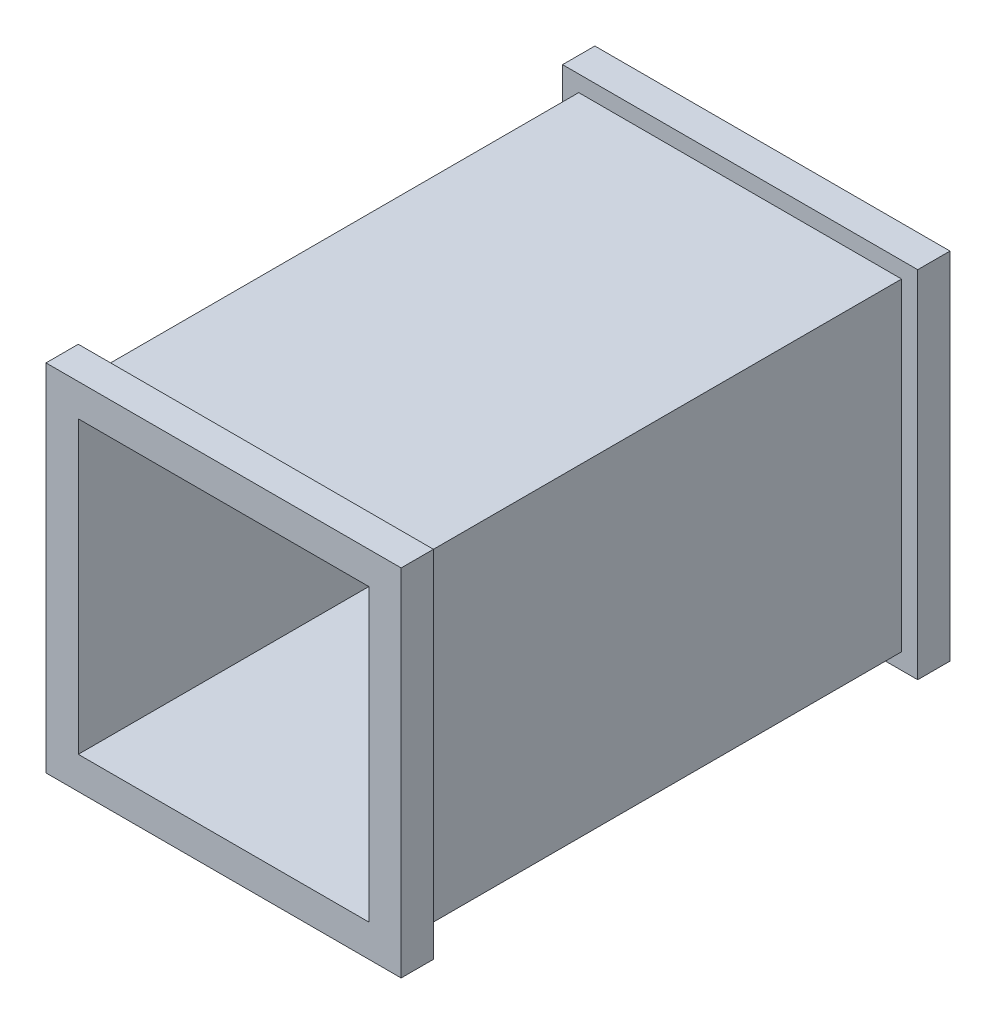
SolidWorks part; units mm, degrees
ref_plane "Front Plane" through (0, 0, 0) normal (0, 0, 1) x (1, 0, 0)
ref_plane "Top Plane" through (0, 0, 0) normal (0, 1, 0) x (1, 0, 0)
ref_plane "Right Plane" through (0, 0, 0) normal (1, 0, 0) x (0, 0, -1)
sketch "Sketch1" plane through (0, 0, 0) normal (0, 0, 1) x (1, 0, 0)
  line L1 (-127, -127) -> (127, -127)
  line L2 (-127, -127) -> (-127, 127)
  line L3 (-127, 127) -> (127, 127)
  line L4 (127, -127) -> (127, 127)
  line L5 (-127, -127) -> (127, 127) construction
  line L6 (-127, 127) -> (127, -127) construction
  point P0 (0, 0)
  dimension "D1" = 254
  dimension "D2" = 254
ref_plane "Plane1" through (0, 0, 381) normal (0, 0, 1) x (1, 0, 0)
sketch "Sketch2" plane through (0, 0, 381) normal (0, 0, 1) x (1, 0, 0)
  line L1 (-127, -127) -> (127, -127)
  line L2 (-127, -127) -> (-127, 127)
  line L3 (-127, 127) -> (127, 127)
  line L4 (127, -127) -> (127, 127)
  line L5 (-127, -127) -> (127, 127) construction
  line L6 (-127, 127) -> (127, -127) construction
  point P0 (0, 0)
loft "Loft1" add profiles "Sketch2", "Sketch1"
sketch "Sketch3" plane through (0, 0, 381) normal (0, 0, 1) x (1, 0, 0)
  line L14 (114.3, -114.3) -> (114.3, 114.3)
  line L15 (-114.3, -114.3) -> (114.3, -114.3)
  line L16 (-114.3, 114.3) -> (-114.3, -114.3)
  line L17 (114.3, 114.3) -> (-114.3, 114.3)
  line L18 (114.3, -114.3) -> (114.3, 114.3)
  line L19 (-114.3, -114.3) -> (114.3, -114.3)
  line L20 (-114.3, 114.3) -> (-114.3, -114.3)
  line L21 (114.3, 114.3) -> (-114.3, 114.3)
  dimension "D1" = 12.7
sketch "Sketch4" plane through (0, 0, 0) normal (0, 0, -1) x (-1, 0, 0)
  line L1 (-114.3, -114.3) -> (114.3, -114.3)
  line L2 (-114.3, -114.3) -> (-114.3, 114.3)
  line L3 (-114.3, 114.3) -> (114.3, 114.3)
  line L4 (114.3, -114.3) -> (114.3, 114.3)
  line L5 (-114.3, -114.3) -> (114.3, 114.3) construction
  line L6 (-114.3, 114.3) -> (114.3, -114.3) construction
  point P0 (0, 0)
loft "Cut-Loft1" cut profiles "Sketch4", "Sketch3"
sketch "Sketch5" plane through (0, 0, 0) normal (0, 0, -1) x (-1, 0, 0)
  line L2 (-114.3, -114.3) -> (114.3, -114.3)
  line L3 (-114.3, -114.3) -> (-114.3, 114.3)
  line L4 (-114.3, 114.3) -> (114.3, 114.3)
  line L5 (114.3, -114.3) -> (114.3, 114.3)
  line L6 (-114.3, -114.3) -> (114.3, 114.3) construction
  line L7 (-114.3, 114.3) -> (114.3, -114.3) construction
  line L21 (139.7, -139.7) -> (139.7, 139.7)
  line L22 (-139.7, -139.7) -> (139.7, -139.7)
  line L23 (-139.7, 139.7) -> (-139.7, -139.7)
  line L24 (139.7, 139.7) -> (-139.7, 139.7)
  line L25 (139.7, -139.7) -> (139.7, 139.7)
  line L26 (-139.7, -139.7) -> (139.7, -139.7)
  line L27 (-139.7, 139.7) -> (-139.7, -139.7)
  line L28 (139.7, 139.7) -> (-139.7, 139.7)
  point P2 (0, 0)
  dimension "D1" = 12.7
extrude "Boss-Extrude1" add sketch "Sketch5" along normal blind 25.4
sketch "Sketch7" plane through (0, 0, 381) normal (0, 0, 1) x (1, 0, 0)
  line L1 (-114.3, -114.3) -> (114.3, -114.3)
  line L2 (-114.3, -114.3) -> (-114.3, 114.3)
  line L3 (-114.3, 114.3) -> (114.3, 114.3)
  line L4 (114.3, -114.3) -> (114.3, 114.3)
  line L5 (-114.3, -114.3) -> (114.3, 114.3) construction
  line L6 (-114.3, 114.3) -> (114.3, -114.3) construction
  line L20 (139.7, -139.7) -> (139.7, 139.7)
  line L21 (-139.7, -139.7) -> (139.7, -139.7)
  line L22 (-139.7, 139.7) -> (-139.7, -139.7)
  line L23 (139.7, 139.7) -> (-139.7, 139.7)
  line L24 (139.7, -139.7) -> (139.7, 139.7)
  line L25 (-139.7, -139.7) -> (139.7, -139.7)
  line L26 (-139.7, 139.7) -> (-139.7, -139.7)
  line L27 (139.7, 139.7) -> (-139.7, 139.7)
  point P0 (0, 0)
  dimension "D1" = 12.7
extrude "Boss-Extrude4" add sketch "Sketch7" along normal blind 25.4
